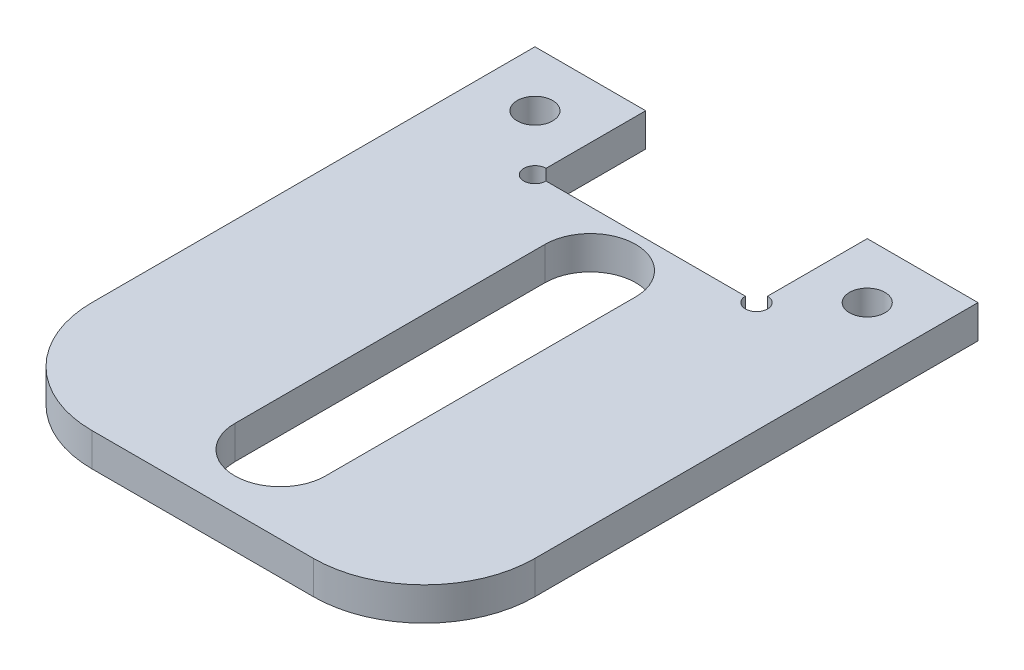
SolidWorks part; units mm, degrees
ref_plane "前视基准面" through (0, 0, 0) normal (0, 0, 1) x (1, 0, 0)
ref_plane "上视基准面" through (0, 0, 0) normal (0, 1, 0) x (1, 0, 0)
ref_plane "右视基准面" through (0, 0, 0) normal (1, 0, 0) x (0, 0, -1)
other "Configuration Table"
sketch "草图1" plane through (0, 0, 0) normal (0, 1, 0) x (1, 0, 0)
  line L0 (-10, 25) -> (-10, 15)
  line L1 (-20, -25) -> (20, -25)
  line L2 (-20, -25) -> (-20, 25)
  line L3 (-20, 25) -> (-10, 25)
  line L4 (20, -25) -> (20, 25)
  line L5 (-20, -25) -> (20, 25) construction
  line L6 (-20, 25) -> (20, -25) construction
  line L7 (-10, 15) -> (10, 15)
  line L8 (10, 15) -> (10, 25)
  line L9 (10, 25) -> (20, 25)
  line L10 (0, 10) -> (0, -18) construction
  line L11 (4.1, 10) -> (4.1, -18)
  line L12 (-4.1, 10) -> (-4.1, -18)
  arc A0 (4.1, 10) -> (-4.1, 10) centre (0, 10) ccw
  arc A1 (-4.1, -18) -> (4.1, -18) centre (0, -18) ccw
  circle A2 centre (-15, 20) radius 1.6
  circle A3 centre (15, 20) radius 1.6
  point P0 (0, 0)
  point P12 (0, -4)
  dimension "D8" = 28
  dimension "D11" = 3.2
  dimension "D14" = 3.2
  dimension "D1" = 40
  dimension "D2" = 50
  dimension "D3" = 10
  dimension "D4" = 10
  dimension "D5" = 10
  dimension "D6" = 8.2
  dimension "D7" = 19
  dimension "D9" = 5
  dimension "D10" = 5
  dimension "D12" = 5
  dimension "D13" = 5
extrude "凸台-拉伸1" add sketch "草图1" along normal blind 3
fillet "圆角1" radius 10 2 edges at (20, 1.5, 25) (-20, 1.5, 25)
sketch "草图2" plane through (0, 3, 0) normal (0, 1, 0) x (1, 0, 0)
  circle A0 centre (-10, 15) radius 1
  circle A1 centre (10, 15) radius 1
  dimension "D1" = 2
  dimension "D2" = 2
extrude "切除-拉伸1" cut sketch "草图2" against normal blind 3
